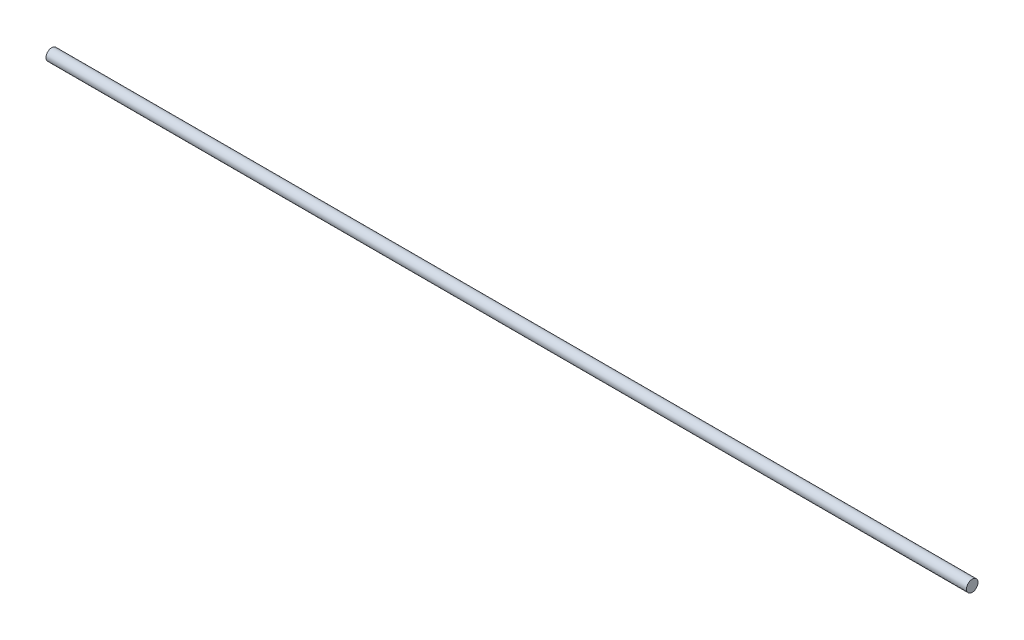
SolidWorks part; units mm, degrees
material "AISI Тип 316L нержавеющая сталь"
ref_plane "Спереди" through (0, 0, 0) normal (0, 0, 1) x (1, 0, 0)
ref_plane "Сверху" through (0, 0, 0) normal (0, 1, 0) x (1, 0, 0)
ref_plane "Справа" through (0, 0, 0) normal (1, 0, 0) x (0, 0, -1)
sketch "Эскиз1" plane through (0, 0, 0) normal (1, 0, 0) x (0, 0, -1)
  line L0 (0, 10) -> (0, -10) construction
  line L1 (0, 10) -> (8.0242, 10) construction
  circle A0 centre (0, 0) radius 10
  dimension "D1" = 20
extrude "Бобышка-Вытянуть1" add sketch "Эскиз1" along normal mid plane 1600
sketch "Эскиз2" plane through (0, 0, 0) normal (0, 0, 1) x (1, 0, 0)
  line L0 (-800, 10) -> (800, 10) construction
  dimension "D1" = 1600
ref_plane "Плоскость1" through (0, 10, 0) normal (0, 1, 0) x (1, 0, 0)
